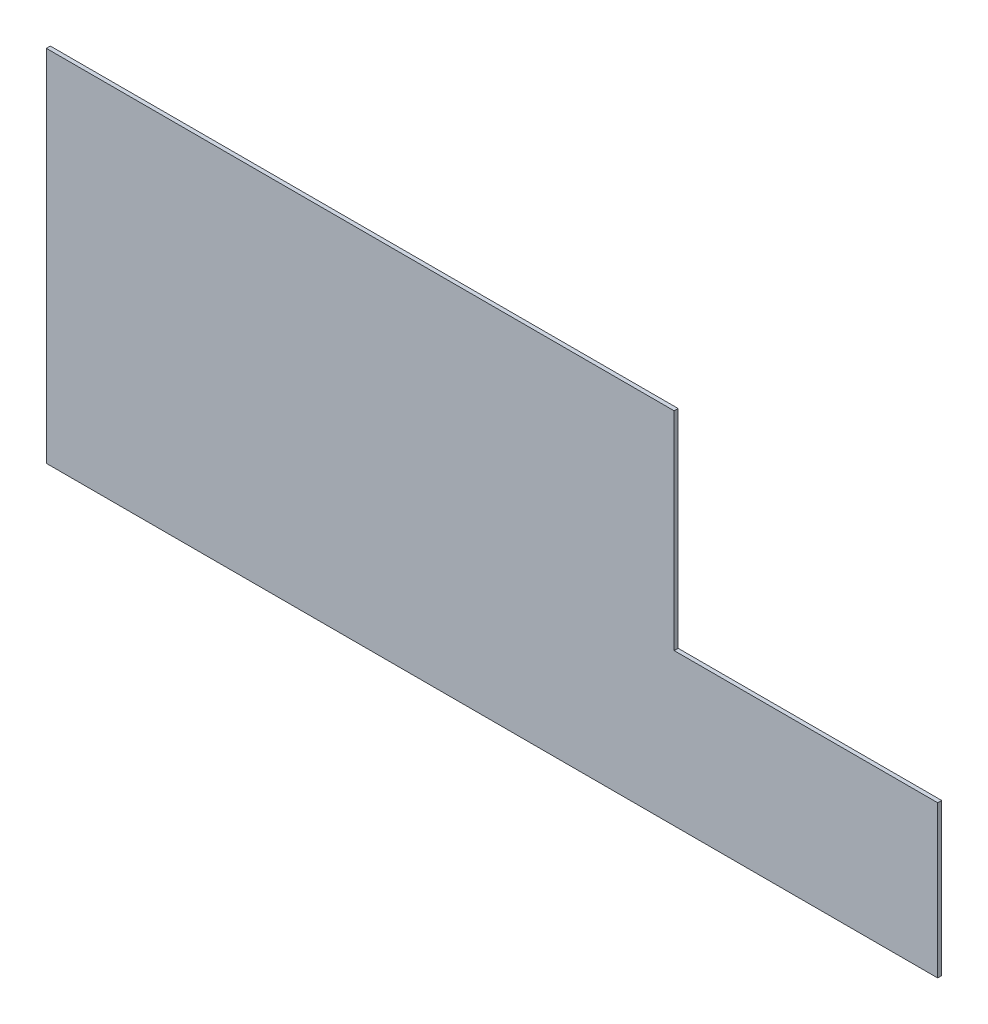
SolidWorks part; units mm, degrees
material "Acrilico (impatto medio-alto)"
ref_plane "Piano frontale" through (0, 0, 0) normal (0, 0, 1) x (1, 0, 0)
ref_plane "Piano superiore" through (0, 0, 0) normal (0, 1, 0) x (1, 0, 0)
ref_plane "Piano destro" through (0, 0, 0) normal (1, 0, 0) x (0, 0, -1)
sketch "Schizzo1" plane through (0, 0, 0) normal (0, 0, 1) x (1, 0, 0)
  line L1 (279, -112.5) -> (-279, -112.5)
  line L2 (279, -112.5) -> (279, 112.5)
  line L3 (279, 112.5) -> (-279, 112.5)
  line L4 (-279, -112.5) -> (-279, 112.5)
  line L5 (279, -112.5) -> (-279, 112.5) construction
  line L6 (279, 112.5) -> (-279, -112.5) construction
  point P4 (0, 0)
  dimension "D1" = 225
  dimension "D2" = 558
extrude "Estrusione-Estrusione1" add sketch "Schizzo1" along normal blind 2.5
sketch "Schizzo2" plane through (0, 0, 0) normal (0, 0, -1) x (-1, 0, 0)
  line L1 (-279, 112.5) -> (-114, 112.5)
  line L2 (-279, 112.5) -> (-279, -17.5)
  line L3 (-279, -17.5) -> (-114, -17.5)
  line L4 (-114, 112.5) -> (-114, -17.5)
  line L5 (-279, 112.5) -> (-114, -17.5) construction
  line L6 (-279, -17.5) -> (-114, 112.5) construction
  line L8 (-279, 112.5) -> (279, 112.5) construction
  line L9 (-279, -112.5) -> (-279, 112.5) construction
  point P4 (-196.5, 47.5)
  point P7 (-259.1788, 112.5)
  dimension "D1" = 130
  dimension "D3" = 165
extrude "Taglio-Estrusione1" cut sketch "Schizzo2" against normal blind 10
